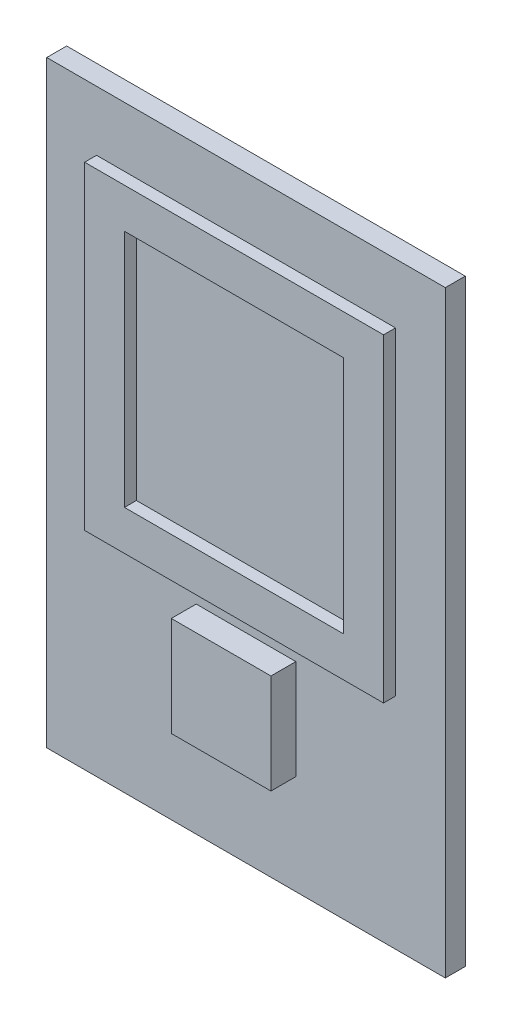
SolidWorks part; units mm, degrees
ref_plane "Plan de face" through (0, 0, 0) normal (0, 0, 1) x (1, 0, 0)
ref_plane "Plan de dessus" through (0, 0, 0) normal (0, 1, 0) x (1, 0, 0)
ref_plane "Plan de droite" through (0, 0, 0) normal (1, 0, 0) x (0, 0, -1)
sketch "Esquisse1" plane through (0, 0, 0) normal (0, 0, 1) x (1, 0, 0)
  line L1 (-20, -30) -> (20, -30)
  line L2 (-20, -30) -> (-20, 30)
  line L3 (-20, 30) -> (20, 30)
  line L4 (20, -30) -> (20, 30)
extrude "PCB_RFID_RC522" add sketch "Esquisse1" along normal blind 2
sketch "Esquisse2" plane through (0, 0, 0) normal (0, 0, 1) x (1, 0, 0)
  line L1 (-15, -8) -> (15, -8)
  line L2 (-15, -8) -> (-15, 24)
  line L3 (-15, 24) -> (15, 24)
  line L4 (15, -8) -> (15, 24)
  line L6 (-11, -4) -> (11, -4)
  line L7 (-11, -4) -> (-11, 20)
  line L8 (-11, 20) -> (11, 20)
  line L9 (11, -4) -> (11, 20)
extrude "Antenne_RFID" add sketch "Esquisse2" along normal blind 1.2 from offset 2
sketch "Esquisse3" plane through (0, 0, 0) normal (0, 0, 1) x (1, 0, 0)
  line L1 (-5, -20) -> (5, -20)
  line L2 (-5, -20) -> (-5, -10)
  line L3 (-5, -10) -> (5, -10)
  line L4 (5, -20) -> (5, -10)
extrude "Puce_MFRC522" add sketch "Esquisse3" along normal blind 2.5 from offset 2
sketch "Esquisse4" plane through (0, 0, 0) normal (0, 0, 1) x (1, 0, 0)
  line L1 (-11, -29) -> (11, -29)
  line L2 (-11, -29) -> (-11, -26)
  line L3 (-11, -26) -> (11, -26)
  line L4 (11, -29) -> (11, -26)
extrude "Connecteur_SPI" add sketch "Esquisse4" against normal blind 5
